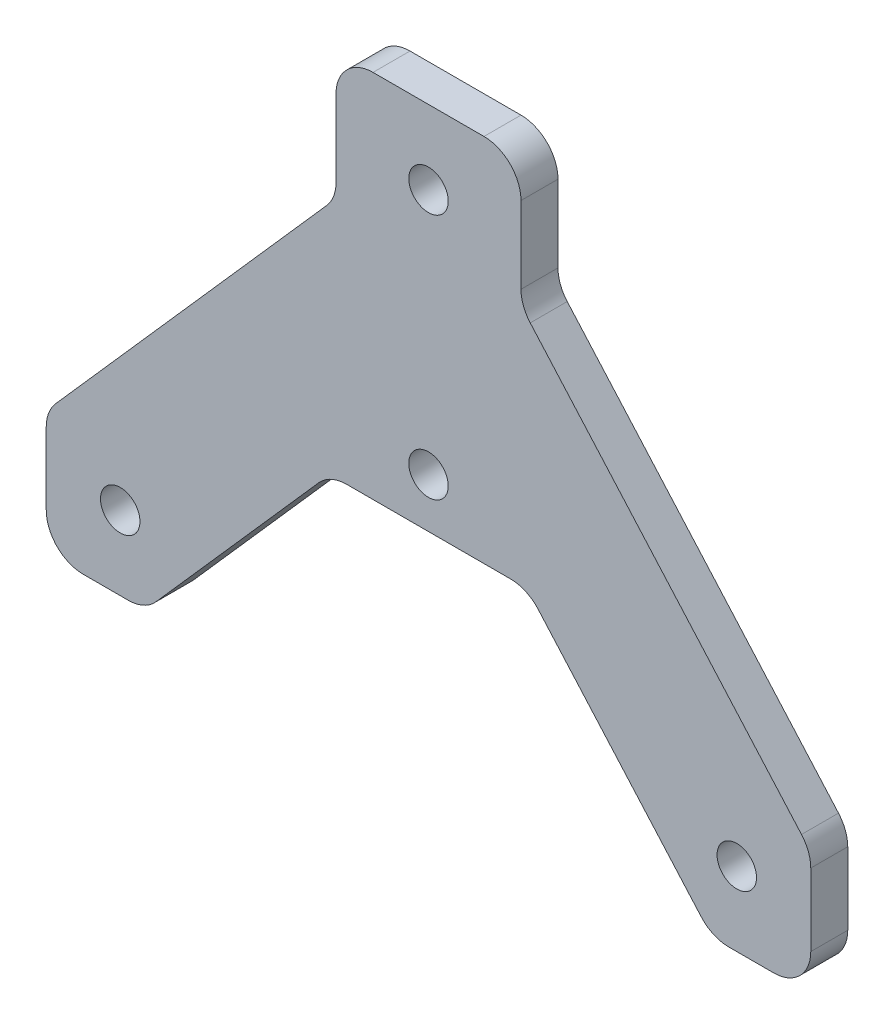
SolidWorks part; units mm, degrees
ref_plane "前视基准面" through (0, 0, 0) normal (0, 0, 1) x (1, 0, 0)
ref_plane "上视基准面" through (0, 0, 0) normal (0, 1, 0) x (1, 0, 0)
ref_plane "右视基准面" through (0, 0, 0) normal (1, 0, 0) x (0, 0, -1)
sketch "草图1" plane through (0, 0, 0) normal (0, 0, 1) x (1, 0, 0)
  line L0 (25, 0) -> (-25, 0) construction
  line L1 (0, 0) -> (0, 35) construction
  line L2 (8, 11) -> (-8, 11)
  line L3 (-8, 11) -> (-23, -6)
  line L4 (-23, -6) -> (-31, -6)
  line L5 (-31, -6) -> (-31, 4)
  line L6 (-31, 4) -> (-7.5, 30.6333)
  line L7 (-7.5, 30.6333) -> (-7.5, 41)
  line L8 (-7.5, 41) -> (7.5, 41)
  line L9 (8, 11) -> (23, -6)
  line L10 (23, -6) -> (31, -6)
  line L11 (31, -6) -> (31, 4)
  line L12 (31, 4) -> (7.5, 30.6333)
  line L13 (7.5, 30.6333) -> (7.5, 41)
  circle A0 centre (-25, 0) radius 1.6
  circle A1 centre (25, 0) radius 1.6
  circle A2 centre (0, 35) radius 1.6
  circle A3 centre (0, 15) radius 1.6
  point P4 (0, 0)
  point P21 (0, 11)
  point P26 (0, 41)
  dimension "D1" = 3.2
  dimension "D2" = 15
  dimension "D3" = 20
  dimension "D6" = 6
  dimension "D9" = 6
  dimension "D4" = 50
  dimension "D5" = 6
  dimension "D7" = 4
  dimension "D8" = 15
  dimension "D10" = 11
  dimension "D11" = 16
  dimension "D12" = 2
extrude "凸台-拉伸1" add sketch "草图1" along normal blind 3
fillet "圆角1" radius 3 12 edges at (23, -6, 1.5) (8, 11, 1.5) (-8, 11, 1.5) (-23, -6, 1.5) (-31, -6, 1.5) (-31, 4, 1.5) (-7.5, 30.6333, 1.5) (-7.5, 41, 1.5) (7.5, 30.6333, 1.5) (31, 4, 1.5) (31, -6, 1.5) (7.5, 41, 1.5)
